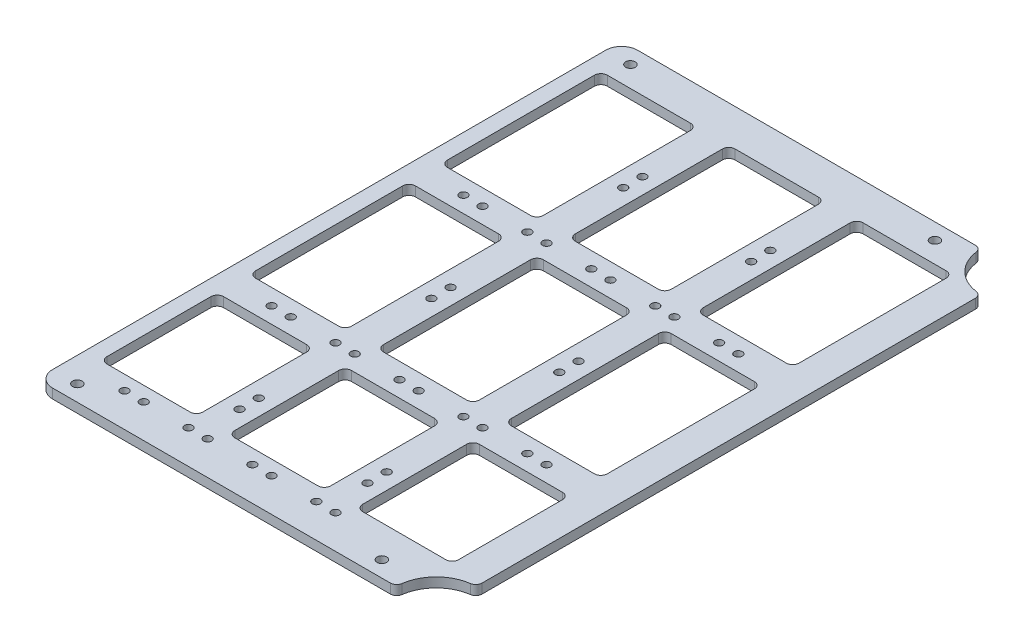
SolidWorks part; units mm, degrees
material "PBT General Purpose"
ref_plane "Front Plane" through (0, 0, 0) normal (0, 0, 1) x (1, 0, 0)
ref_plane "Top Plane" through (0, 0, 0) normal (0, 1, 0) x (1, 0, 0)
ref_plane "Right Plane" through (0, 0, 0) normal (1, 0, 0) x (0, 0, -1)
sketch "Sketch1" plane through (0, 0, 0) normal (0, 1, 0) x (1, 0, 0)
  line L0 (205, 183) -> (205, 0) construction
  line L2 (0, 14.3614) -> (0, 168.6386)
  line L3 (14.3614, 183) -> (395.6386, 183)
  line L4 (410, 14.3614) -> (410, 168.6386)
  line L5 (0, 91.5) -> (410, 91.5) construction
  line L6 (0, 183) -> (0, 170.5) construction
  line L7 (0, 183) -> (12.5, 183) construction
  line L8 (14.3614, 0) -> (395.6386, 0)
  arc A0 (12.3805, 181.2759) -> (1.7241, 170.6195) centre (0, 183) cw
  arc A1 (397.6195, 181.2759) -> (408.2759, 170.6195) centre (410, 183) ccw
  arc A2 (397.6195, 1.7241) -> (408.2759, 12.3805) centre (410, 0) cw
  arc A3 (12.3805, 1.7241) -> (1.7241, 12.3805) centre (0, 0) ccw
  arc A4 (14.3614, 183) -> (12.3805, 181.2759) centre (14.3614, 181) ccw
  arc A5 (1.7241, 170.6195) -> (0, 168.6386) centre (2, 168.6386) ccw
  arc A6 (0, 14.3614) -> (1.7241, 12.3805) centre (2, 14.3614) ccw
  arc A7 (12.3805, 1.7241) -> (14.3614, 0) centre (14.3614, 2) ccw
  arc A8 (395.6386, 0) -> (397.6195, 1.7241) centre (395.6386, 2) ccw
  arc A9 (408.2759, 12.3805) -> (410, 14.3614) centre (408, 14.3614) ccw
  arc A10 (408.2759, 170.6195) -> (410, 168.6386) centre (408, 168.6386) cw
  arc A11 (397.6195, 181.2759) -> (395.6386, 183) centre (395.6386, 181) ccw
  point P26 (0, 12.5)
  point P29 (12.5, 0)
  point P32 (397.5, 0)
  point P35 (410, 12.5)
  point P38 (410, 170.5)
  point P41 (397.5, 183)
  dimension "D3" = 91.5
  dimension "D5" = 12.5
  dimension "D6" = 2
  dimension "D1" = 183
  dimension "D2" = 410
  dimension "D4" = 205
extrude "Boss-Extrude1" add sketch "Sketch1" along normal blind 3
sketch "Sketch10" plane through (0, 3, 0) normal (0, 1, 0) x (1, 0, 0)
  line L0 (17.5, 178) -> (388, 178) construction
  line L1 (388, 178) -> (388, 5) construction
  line L2 (388, 5) -> (17.5, 5) construction
  line L3 (17.5, 5) -> (17.5, 178) construction
  line L4 (395.6386, 183) -> (14.3614, 183) construction
  line L5 (14.3614, 0) -> (395.6386, 0) construction
  line L6 (0, 168.6386) -> (0, 14.3614) construction
  line L7 (410, 14.3614) -> (410, 168.6386) construction
  line L8 (202.75, 178) -> (292.75, 178) construction
  circle A0 centre (17.5, 178) radius 1.5
  circle A1 centre (388, 178) radius 1.5
  circle A2 centre (388, 5) radius 1.5
  circle A3 centre (17.5, 5) radius 1.5
  circle A4 centre (202.75, 178) radius 1.5
  circle A5 centre (202.75, 5) radius 1.5
  circle A6 centre (292.75, 178) radius 1.5
  circle A7 centre (292.75, 5) radius 1.5
  dimension "D5" = 3
  dimension "D8" = 3
  dimension "D1" = 5
  dimension "D2" = 5
  dimension "D3" = 17.5
  dimension "D4" = 22
  dimension "D7" = 90
  dimension "D6" = 2
extrude "Cut-Extrude6" cut sketch "Sketch10" against normal up to next
sketch "Sketch11" plane through (0, 3, 0) normal (0, 1, 0) x (1, 0, 0)
  line L0 (395.6386, 183) -> (14.3614, 183) construction
  line L1 (0, 0) -> (285, 0)
  line L2 (0, 0) -> (0, 183)
  line L3 (0, 183) -> (285, 183)
  line L4 (285, 0) -> (285, 183)
  line L5 (410, 14.3614) -> (410, 168.6386) construction
  dimension "D1" = 125
extrude "Cut-Extrude7" cut sketch "Sketch11" against normal blind 10
fillet "Fillet1" radius 5 2 edges at (285, 1.5, -183) (285, 1.5, 0)
sketch "Sketch12" plane through (0, 3, 0) normal (0, 1, 0) x (1, 0, 0)
  line L0 (285, 181.5) -> (410, 181.5) construction
  line L1 (395.6386, 183) -> (290, 183) construction
  line L2 (285, 186.6919) -> (285, 0) construction
  line L3 (410, 186.6919) -> (410, 0) construction
  line L4 (285, 5) -> (285, 178) construction
  line L5 (410, 14.3614) -> (410, 168.6386) construction
  line L6 (285, 171.5) -> (410, 171.5) construction
  line L7 (332, 121.5) -> (358, 121.5)
  line L8 (292, 171.5) -> (318, 171.5)
  line L9 (290, 169.5) -> (290, 123.5)
  line L10 (292, 121.5) -> (318, 121.5)
  line L11 (320, 169.5) -> (320, 123.5)
  line L12 (360, 169.5) -> (360, 123.5)
  line L13 (332, 171.5) -> (358, 171.5)
  line L14 (330, 169.5) -> (330, 123.5)
  line L15 (372, 121.5) -> (398, 121.5)
  line L16 (400, 169.5) -> (400, 123.5)
  line L17 (372, 171.5) -> (398, 171.5)
  line L18 (370, 169.5) -> (370, 123.5)
  line L19 (290, 121.5) -> (330, 121.5) construction
  line L20 (320, 146.5) -> (330, 146.5) construction
  line L21 (370, 146.5) -> (404.9149, 146.5) construction
  line L22 (325, 149.5) -> (365, 149.5) construction
  line L35 (332, 61.5) -> (358, 61.5)
  line L48 (292, 111.5) -> (318, 111.5)
  line L61 (290, 109.5) -> (290, 63.5)
  line L74 (292, 61.5) -> (318, 61.5)
  line L87 (320, 109.5) -> (320, 63.5)
  line L100 (360, 109.5) -> (360, 63.5)
  line L101 (332, 111.5) -> (358, 111.5)
  line L102 (330, 109.5) -> (330, 63.5)
  line L103 (372, 61.5) -> (398, 61.5)
  line L104 (400, 109.5) -> (400, 63.5)
  line L105 (372, 111.5) -> (398, 111.5)
  line L106 (370, 109.5) -> (370, 63.5)
  line L107 (285, 111.5) -> (410, 111.5) construction
  line L108 (290, 61.5) -> (330, 61.5) construction
  line L109 (320, 86.5) -> (330, 86.5) construction
  line L110 (370, 86.5) -> (404.9149, 86.5) construction
  line L111 (325, 89.5) -> (365, 89.5) construction
  line L113 (292, 51.5) -> (318, 51.5)
  line L114 (290, 49.5) -> (290, 17)
  line L116 (320, 49.5) -> (320, 17)
  line L117 (360, 49.5) -> (360, 17)
  line L118 (332, 51.5) -> (358, 51.5)
  line L119 (330, 49.5) -> (330, 17)
  line L121 (400, 49.5) -> (400, 17)
  line L122 (372, 51.5) -> (398, 51.5)
  line L123 (370, 49.5) -> (370, 17)
  line L124 (285, 51.5) -> (410, 51.5) construction
  line L125 (305, 121.5) -> (305, 111.5) construction
  line L126 (320, 26.5) -> (330, 26.5) construction
  line L127 (370, 26.5) -> (404.9149, 26.5) construction
  line L128 (325, 29.5) -> (365, 29.5) construction
  line L129 (332, 121.5) -> (332, 61.5) construction
  line L130 (292, 15) -> (318, 15)
  line L131 (290, 0) -> (395.6386, 0) construction
  line L132 (332, 15) -> (358, 15)
  line L133 (372, 15) -> (398, 15)
  line L134 (302, 116.5) -> (322, 116.5) construction
  line L135 (305, 61.5) -> (305, 51.5) construction
  line L136 (332, 61.5) -> (332, 1.5) construction
  line L137 (302, 56.5) -> (322, 56.5) construction
  line L138 (302, 116.5) -> (302, 56.5) construction
  line L139 (305, 15.5) -> (305, 5.5) construction
  line L140 (332, 15.5) -> (332, -44.5) construction
  line L141 (302, 10.5) -> (322, 10.5) construction
  line L142 (302, 70.5) -> (302, 10.5) construction
  line L143 (302, 56.5) -> (302, 10.5) construction
  line L180 (292, 1.5) -> (318, 1.5) [skipped]
  line L181 (318, 1.5) -> (330, 1.5) construction
  line L182 (332, 1.5) -> (358, 1.5) [skipped]
  line L183 (372, 1.5) -> (398, 1.5) [skipped]
  arc A0 (370, 123.5) -> (372, 121.5) centre (372, 123.5) ccw
  arc A1 (398, 121.5) -> (400, 123.5) centre (398, 123.5) ccw
  arc A2 (400, 169.5) -> (398, 171.5) centre (398, 169.5) ccw
  arc A3 (372, 171.5) -> (370, 169.5) centre (372, 169.5) ccw
  arc A4 (358, 171.5) -> (360, 169.5) centre (358, 169.5) cw
  arc A5 (360, 123.5) -> (358, 121.5) centre (358, 123.5) cw
  arc A6 (330, 123.5) -> (332, 121.5) centre (332, 123.5) ccw
  arc A7 (330, 169.5) -> (332, 171.5) centre (332, 169.5) cw
  arc A8 (290, 123.5) -> (292, 121.5) centre (292, 123.5) ccw
  arc A9 (320, 169.5) -> (318, 171.5) centre (318, 169.5) ccw
  arc A10 (320, 123.5) -> (318, 121.5) centre (318, 123.5) cw
  arc A11 (290, 169.5) -> (292, 171.5) centre (292, 169.5) cw
  circle A12 centre (325, 149.5) radius 1.25
  circle A13 centre (325, 143.5) radius 1.25
  circle A14 centre (365, 149.5) radius 1.25
  circle A15 centre (365, 143.5) radius 1.25
  arc A112 (370, 63.5) -> (372, 61.5) centre (372, 63.5) ccw
  arc A113 (398, 61.5) -> (400, 63.5) centre (398, 63.5) ccw
  arc A114 (400, 109.5) -> (398, 111.5) centre (398, 109.5) ccw
  arc A115 (372, 111.5) -> (370, 109.5) centre (372, 109.5) ccw
  arc A116 (358, 111.5) -> (360, 109.5) centre (358, 109.5) cw
  arc A117 (360, 63.5) -> (358, 61.5) centre (358, 63.5) cw
  arc A118 (330, 63.5) -> (332, 61.5) centre (332, 63.5) ccw
  arc A119 (330, 109.5) -> (332, 111.5) centre (332, 109.5) cw
  arc A120 (290, 63.5) -> (292, 61.5) centre (292, 63.5) ccw
  arc A121 (320, 109.5) -> (318, 111.5) centre (318, 109.5) ccw
  arc A122 (320, 63.5) -> (318, 61.5) centre (318, 63.5) cw
  arc A123 (290, 109.5) -> (292, 111.5) centre (292, 109.5) cw
  circle A124 centre (325, 89.5) radius 1.25
  circle A125 centre (325, 83.5) radius 1.25
  circle A126 centre (365, 89.5) radius 1.25
  circle A127 centre (365, 83.5) radius 1.25
  arc A130 (400, 49.5) -> (398, 51.5) centre (398, 49.5) ccw
  arc A131 (372, 51.5) -> (370, 49.5) centre (372, 49.5) ccw
  arc A132 (358, 51.5) -> (360, 49.5) centre (358, 49.5) cw
  arc A135 (330, 49.5) -> (332, 51.5) centre (332, 49.5) cw
  arc A137 (320, 49.5) -> (318, 51.5) centre (318, 49.5) ccw
  arc A139 (290, 49.5) -> (292, 51.5) centre (292, 49.5) cw
  circle A140 centre (325, 29.5) radius 1.25
  circle A141 centre (325, 23.5) radius 1.25
  circle A142 centre (365, 29.5) radius 1.25
  circle A143 centre (365, 23.5) radius 1.25
  arc A144 (398, 15) -> (400, 17) centre (398, 17) ccw
  arc A145 (372, 15) -> (370, 17) centre (372, 17) cw
  arc A146 (360, 17) -> (358, 15) centre (358, 17) cw
  arc A147 (332, 15) -> (330, 17) centre (332, 17) cw
  arc A148 (320, 17) -> (318, 15) centre (318, 17) cw
  arc A149 (292, 15) -> (290, 17) centre (292, 17) cw
  circle A150 centre (302, 116.5) radius 1.25
  circle A151 centre (308, 116.5) radius 1.25
  circle A152 centre (322, 116.5) radius 1.25
  circle A153 centre (328, 116.5) radius 1.25
  circle A154 centre (342, 116.5) radius 1.25
  circle A155 centre (348, 116.5) radius 1.25
  circle A156 centre (362, 116.5) radius 1.25
  circle A157 centre (368, 116.5) radius 1.25
  circle A158 centre (382, 116.5) radius 1.25
  circle A159 centre (388, 116.5) radius 1.25
  circle A160 centre (302, 56.5) radius 1.25
  circle A161 centre (308, 56.5) radius 1.25
  circle A162 centre (322, 56.5) radius 1.25
  circle A163 centre (328, 56.5) radius 1.25
  circle A164 centre (342, 56.5) radius 1.25
  circle A165 centre (348, 56.5) radius 1.25
  circle A166 centre (362, 56.5) radius 1.25
  circle A167 centre (368, 56.5) radius 1.25
  circle A168 centre (382, 56.5) radius 1.25
  circle A169 centre (388, 56.5) radius 1.25
  circle A170 centre (302, 10.5) radius 1.25
  circle A171 centre (308, 10.5) radius 1.25
  circle A172 centre (322, 10.5) radius 1.25
  circle A173 centre (328, 10.5) radius 1.25
  circle A174 centre (342, 10.5) radius 1.25
  circle A175 centre (348, 10.5) radius 1.25
  circle A176 centre (362, 10.5) radius 1.25
  circle A177 centre (368, 10.5) radius 1.25
  arc A208 (290, 3.5) -> (292, 1.5) centre (292, 3.5) ccw [skipped]
  arc A209 (320, 3.5) -> (318, 1.5) centre (318, 3.5) cw [skipped]
  arc A210 (330, 3.5) -> (332, 1.5) centre (332, 3.5) ccw [skipped]
  arc A211 (360, 3.5) -> (358, 1.5) centre (358, 3.5) cw [skipped]
  arc A212 (370, 3.5) -> (372, 1.5) centre (372, 3.5) ccw [skipped]
  arc A213 (398, 1.5) -> (400, 3.5) centre (398, 3.5) ccw [skipped]
  circle A214 centre (382, 10.5) radius 1.25 [skipped]
  circle A215 centre (388, 10.5) radius 1.25 [skipped]
  point P42 (330, 121.5)
  point P47 (290, 121.5)
  point P52 (320, 121.5)
  point P55 (290, 171.5)
  point P152 (330, 15)
  dimension "D8" = 60
  dimension "D9" = 2.5
  dimension "D4" = 2
  dimension "D15" = 2
  dimension "D16" = 2.5
  dimension "D1" = 1.5
  dimension "D2" = 10
  dimension "D3" = 50
  dimension "D5" = 30
  dimension "D7" = 40
  dimension "D10" = 6
  dimension "D12" = 40
  dimension "D14" = 15
  dimension "D17" = 3
  dimension "D18" = 20
  dimension "D19" = 60
  dimension "D20" = 46
  dimension "D6" = 3
  dimension "D11" = 2
  dimension "D13" = 3
extrude "Cut-Extrude8" cut sketch "Sketch12" against normal up to next (3 mm away)
